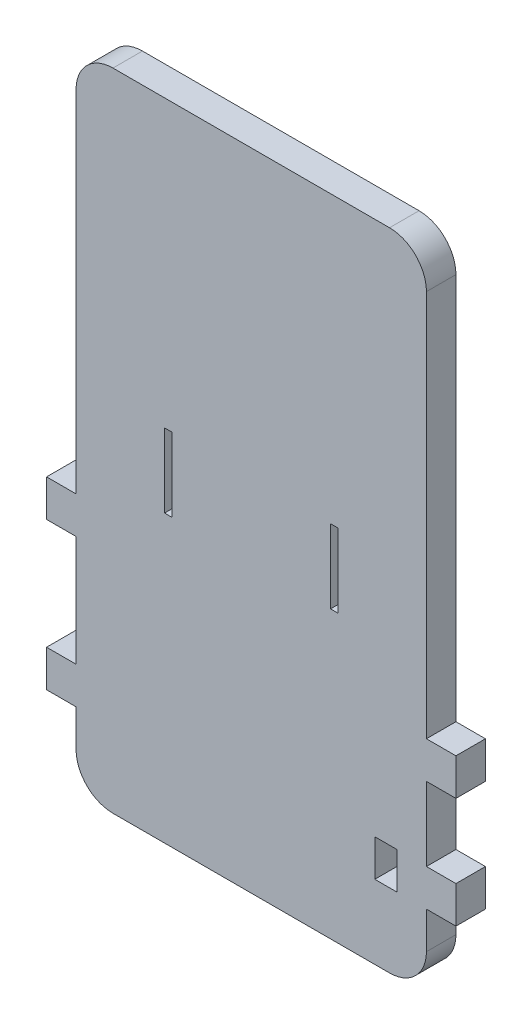
SolidWorks part; units mm, degrees
material "Beech"
ref_plane "Front" through (0, 0, 0) normal (0, 0, 1) x (1, 0, 0)
ref_plane "Top" through (0, 0, 0) normal (0, 1, 0) x (1, 0, 0)
ref_plane "Right" through (0, 0, 0) normal (1, 0, 0) x (0, 0, -1)
sketch "Sketch1" plane through (0, 0, 0) normal (0, 0, 1) x (1, 0, 0)
  line L0 (0, 22.3837) -> (0, -18.314) construction
  line L1 (-37.5, -87.5) -> (37.5, -87.5)
  line L2 (-47.5, -77.5) -> (-47.5, 77.5)
  line L3 (-37.5, 87.5) -> (37.5, 87.5)
  line L4 (47.5, -77.5) -> (47.5, 77.5)
  line L5 (-47.5, -87.5) -> (47.5, 87.5) construction
  line L6 (-47.5, 87.5) -> (47.5, -87.5) construction
  line L7 (-21.5, 10) -> (-23.5, 10)
  line L8 (21.5, -10) -> (23.5, -10)
  line L9 (21.5, -10) -> (21.5, 10)
  line L10 (21.5, 10) -> (23.5, 10)
  line L11 (23.5, -10) -> (23.5, 10)
  line L12 (21.5, -10) -> (23.5, 10) construction
  line L13 (21.5, 10) -> (23.5, -10) construction
  line L14 (-23.5, -10) -> (-23.5, 10)
  line L15 (-21.5, -10) -> (-23.5, -10)
  line L16 (-21.5, -10) -> (-21.5, 10)
  line L17 (47.5, 82.5) -> (-47.5, 82.5) construction
  line L18 (11.0081, 0) -> (-11.7376, 0) construction
  line L20 (33.5, -67.5) -> (39.5, -67.5)
  line L21 (33.5, -67.5) -> (33.5, -57.5)
  line L22 (33.5, -57.5) -> (39.5, -57.5)
  line L23 (39.5, -67.5) -> (39.5, -57.5)
  line L24 (33.5, -67.5) -> (39.5, -57.5) construction
  line L25 (33.5, -57.5) -> (39.5, -67.5) construction
  arc A0 (-37.5, -87.5) -> (-47.5, -77.5) centre (-37.5, -77.5) cw
  arc A1 (37.5, -87.5) -> (47.5, -77.5) centre (37.5, -77.5) ccw
  arc A2 (-47.5, 77.5) -> (-37.5, 87.5) centre (-37.5, 77.5) cw
  arc A3 (37.5, 87.5) -> (47.5, 77.5) centre (37.5, 77.5) cw
  point P0 (0, 0)
  point P8 (22.5, 0)
  point P33 (36.5, -62.5)
  dimension "D7" = 10
  dimension "D1" = 175
  dimension "D2" = 95
  dimension "D3" = 2
  dimension "D4" = 22.5
  dimension "D5" = 20
  dimension "D6" = 5
  dimension "D8" = 10
  dimension "D9" = 25
  dimension "D10" = 6
  dimension "D11" = 8
extrude "Boss-Extrude1" add sketch "Sketch1" along normal blind 8 contours L1 L4 L3 L2 L16 L15 L14 L7 L11 L8 L9 L10
sketch "Sketch3" plane through (-47.5, 0, 0) normal (-1, 0, 0) x (0, 0, 1)
  line L0 (0, -77.5) -> (0, 77.5) construction
  line L1 (0, -57.5) -> (8, -57.5)
  line L2 (0, -57.5) -> (0, -67.5)
  line L3 (0, -67.5) -> (8, -67.5)
  line L4 (8, -57.5) -> (8, -67.5)
  line L5 (0, -57.5) -> (8, -67.5) construction
  line L6 (0, -67.5) -> (8, -57.5) construction
  line L7 (8, -77.5) -> (8, 77.5) construction
  line L9 (8, -87.5) -> (0, -87.5) construction
  line L11 (0, -27.5) -> (8, -27.5)
  line L12 (0, -27.5) -> (0, -17.5)
  line L13 (0, -17.5) -> (8, -17.5)
  line L14 (8, -27.5) -> (8, -17.5)
  line L15 (0, -27.5) -> (8, -17.5) construction
  line L16 (0, -17.5) -> (8, -27.5) construction
  point P4 (4, -62.5)
  point P15 (4, -22.5)
  dimension "D1" = 20
  dimension "D2" = 10
  dimension "D3" = 10
  dimension "D4" = 50
extrude "Boss-Extrude2" add sketch "Sketch3" along normal blind 8
sketch "Sketch4" plane through (47.5, 0, 0) normal (1, 0, 0) x (0, 0, -1)
  line L0 (-8, -77.5) -> (-8, 77.5) construction
  line L1 (-8, -67.5) -> (0, -67.5)
  line L2 (-8, -67.5) -> (-8, -57.5)
  line L3 (-8, -57.5) -> (0, -57.5)
  line L4 (0, -67.5) -> (0, -57.5)
  line L5 (-8, -67.5) -> (0, -57.5) construction
  line L6 (-8, -57.5) -> (0, -67.5) construction
  line L7 (0, -77.5) -> (0, 77.5) construction
  line L8 (-8, -87.5) -> (0, -87.5) construction
  line L9 (-8, -27.5) -> (0, -27.5)
  line L10 (0, -37.5) -> (0, -27.5)
  line L11 (-8, -37.5) -> (0, -37.5)
  line L12 (-8, -37.5) -> (-8, -27.5)
  point P4 (-4, -62.5)
  dimension "D1" = 20
  dimension "D2" = 10
  dimension "D4" = 20
  dimension "D3" = 2
extrude "Boss-Extrude3" add sketch "Sketch4" along normal blind 8
ref_point "Point1"
sketch "Sketch6" plane through (55.5, 0, 0) normal (1, 0, 0) x (0, 0, -1)
  circle A0 centre (-4, -62.5) radius 1.5
  point P3 (0, 0)
  dimension "D1" = 3
